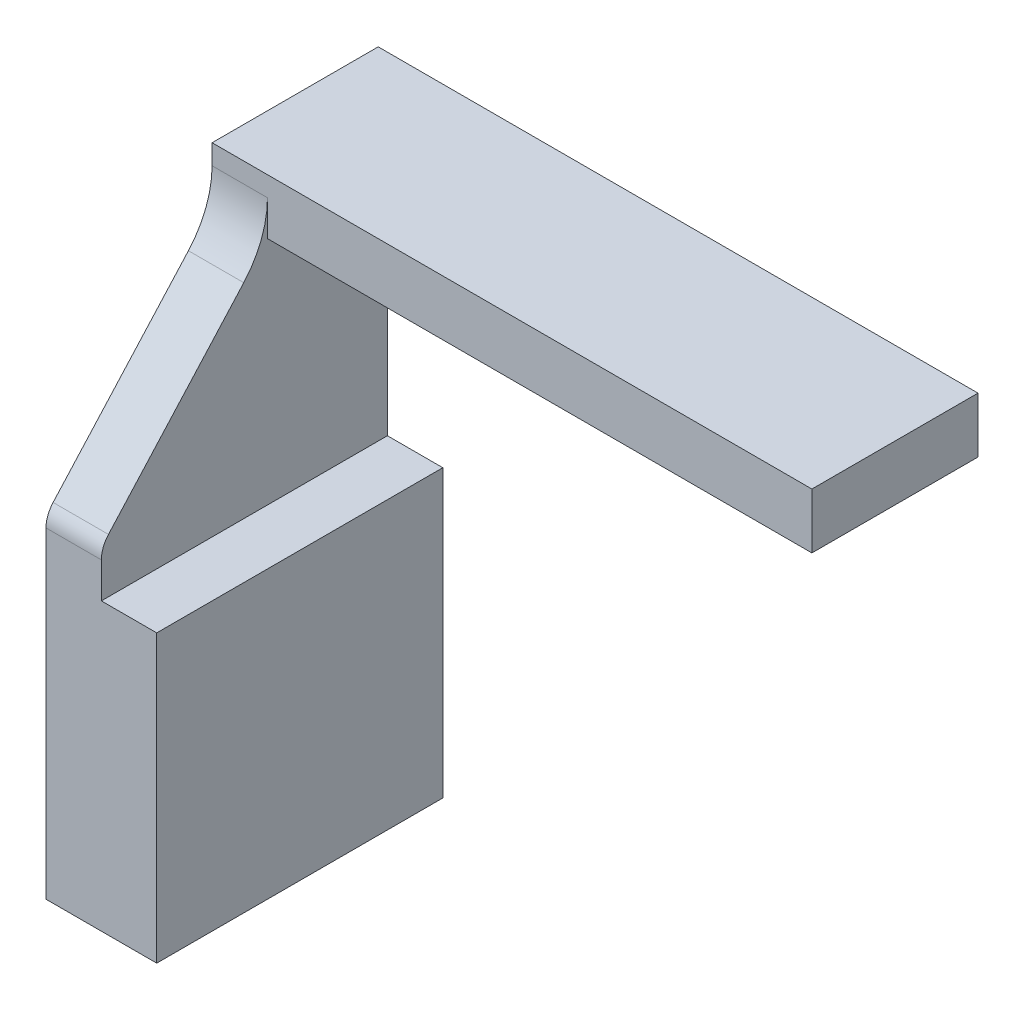
SolidWorks part; units mm, degrees
ref_plane "Front Plane" through (0, 0, 0) normal (0, 0, 1) x (1, 0, 0)
ref_plane "Top Plane" through (0, 0, 0) normal (0, 1, 0) x (1, 0, 0)
ref_plane "Right Plane" through (0, 0, 0) normal (1, 0, 0) x (0, 0, -1)
sketch "Sketch1" plane through (0, 0, 0) normal (0, 1, 0) x (1, 0, 0)
  line L1 (-32.5, -9) -> (32.5, -9)
  line L2 (-32.5, -9) -> (-32.5, 9)
  line L3 (-32.5, 9) -> (32.5, 9)
  line L4 (32.5, -9) -> (32.5, 9)
  line L5 (-32.5, -9) -> (32.5, 9) construction
  line L6 (-32.5, 9) -> (32.5, -9) construction
  point P0 (0, 0)
  dimension "D1" = 18
  dimension "D2" = 65
extrude "Boss-Extrude1" add sketch "Sketch1" along normal blind 6
ref_plane "Plane1" through (-32.5, 0, 0) normal (-1, 0, 0) x (0, 0, 1)
sketch "Sketch2" plane through (-32.5, 0, 0) normal (-1, 0, 0) x (0, 0, 1)
  line L0 (9, 0) -> (-9, 0)
  line L1 (-9, 6) -> (-9, 0) construction
  line L2 (-4, -5) -> (-4, -56)
  line L4 (-4, -56) -> (27, -56)
  line L5 (27, -56) -> (27, -20)
  line L6 (27, -20) -> (9, 0)
  line L7 (-9, 0) -> (-4, -5)
  dimension "D1" = 20
  dimension "D2" = 5
  dimension "D3" = 31
  dimension "D4" = 36
  dimension "D5" = 5
extrude "Boss-Extrude2" add sketch "Sketch2" against normal blind 6
fillet "Fillet1" radius 10 1 edges
fillet "Fillet3" radius 3 2 edges at (-29.5, -20, 27) (-29.5, -5, -4)
ref_plane "Plane2" through (-26.5, 0, 0) normal (1, 0, 0) x (0, 0, -1)
sketch "Sketch3" plane through (-26.5, 0, 0) normal (1, 0, 0) x (0, 0, -1)
  line L0 (-27, -56) -> (-27, -21.1512) construction
  line L1 (4, -56) -> (-27, -56)
  line L2 (4, -56) -> (4, -25)
  line L3 (4, -25) -> (-27, -25)
  line L4 (-27, -56) -> (-27, -25)
  dimension "D1" = 31
extrude "Boss-Extrude3" add sketch "Sketch3" along normal blind 6
